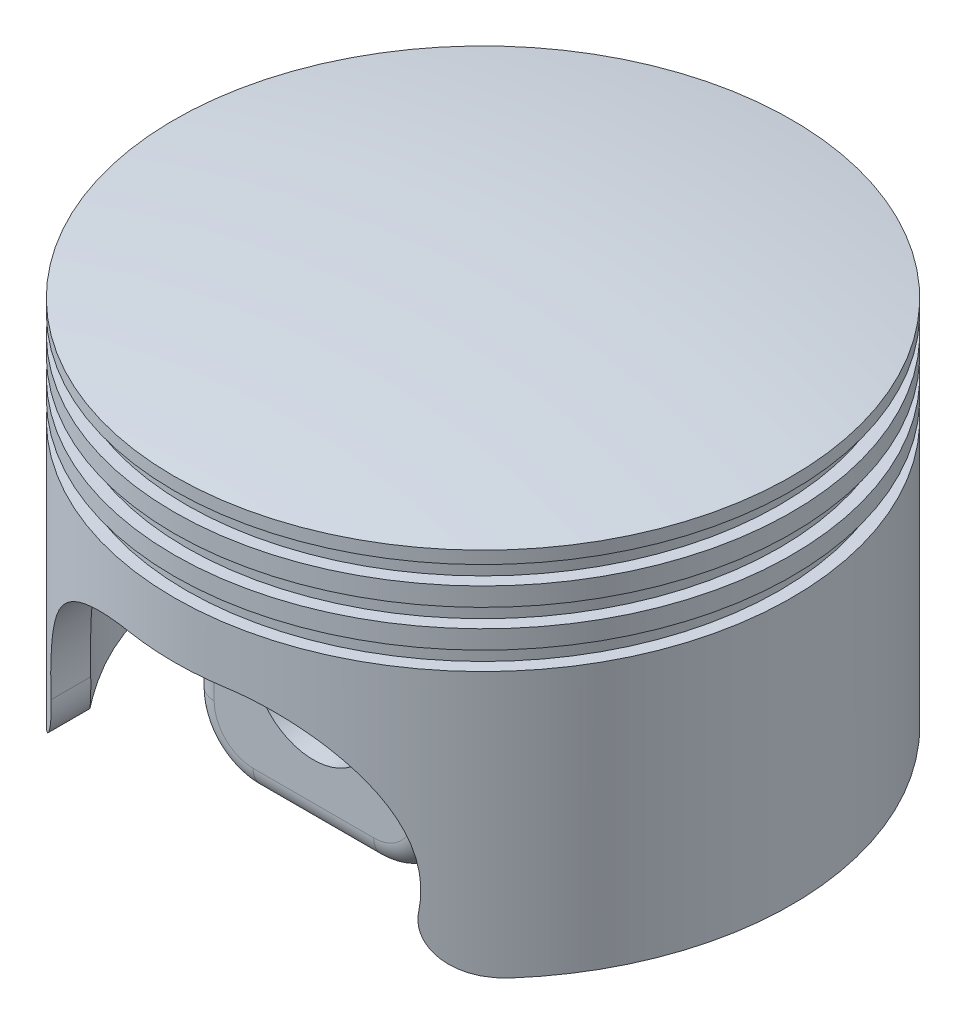
SolidWorks part; units mm, degrees
material "1060 Alloy"
ref_plane "Front Plane" through (0, 0, 0) normal (0, 0, 1) x (1, 0, 0)
ref_plane "Top Plane" through (0, 0, 0) normal (0, 1, 0) x (1, 0, 0)
ref_plane "Right Plane" through (0, 0, 0) normal (1, 0, 0) x (0, 0, -1)
sketch "Sketch1" plane through (0, 0, 0) normal (1, 0, 0) x (0, 0, -1)
  line L0 (0, 0) -> (0, -319.45) construction
  line L1 (-112.706, 0) -> (121.6573, 0) construction
  line L22 (63.5, 0) -> (63.5, 54.66)
  line L23 (63.5, 54.66) -> (60.96, 54.66)
  line L24 (60.96, 54.66) -> (60.96, 58.47)
  line L25 (60.96, 58.47) -> (63.5, 58.47)
  line L26 (63.5, 58.47) -> (63.5, 62.28)
  line L27 (63.5, 62.28) -> (60.96, 62.28)
  line L28 (60.96, 62.28) -> (60.96, 66.09)
  line L29 (60.96, 66.09) -> (63.5, 66.09)
  line L30 (63.5, 66.09) -> (63.5, 69.9)
  line L31 (63.5, 69.9) -> (60.96, 69.9)
  line L32 (60.96, 69.9) -> (60.96, 73.71)
  line L33 (60.96, 73.71) -> (63.5, 73.71)
  line L34 (63.5, 73.71) -> (63.5, 76.28)
  line L36 (0, 76.28) -> (0, 62.28)
  line L37 (0, 76.28) -> (0, 81.28)
  line L38 (63.5, 0) -> (57.15, 0)
  line L39 (57.15, 0) -> (57.15, 62.28)
  line L40 (57.15, 62.28) -> (0, 62.28)
  arc A1 (63.5, 76.28) -> (0, 81.28) centre (-0.0004, -324.45) ccw
  dimension "D2" = 3.81
  dimension "D3" = 3.81
  dimension "D6" = 405.73
  dimension "D9" = 19
  dimension "D1" = 127
  dimension "D4" = 5
  dimension "D5" = 2.54
  dimension "D7" = 81.28
  dimension "D8" = 6.35
revolve "Revolve2" add sketch "Sketch1" angle 360 about L0
sketch "Sketch2" plane through (0, 0, 0) normal (0, 0, 1) x (1, 0, 0)
  line L0 (-10.06, 43.18) -> (10.06, 43.18)
  line L1 (-63.5, 0) -> (63.5, 0) construction
  line L3 (0, 98.8018) -> (0, -12.7881) construction
  line L4 (63.5, 0) -> (47.7053, 0)
  line L5 (-63.5, 0) -> (-47.7053, 0)
  line L6 (-47.7053, 0) -> (47.7053, 0)
  arc A0 (10.06, 43.18) -> (37.7986, 11.3632) centre (10.06, 15.18) cw
  arc A1 (37.7986, 11.3632) -> (47.7053, 0) centre (47.7053, 10) ccw
  arc A2 (-37.7986, 11.3632) -> (-47.7053, 0) centre (-47.7053, 10) cw
  arc A3 (-10.06, 43.18) -> (-37.7986, 11.3632) centre (-10.06, 15.18) ccw
  dimension "D3" = 28
  dimension "D4" = 10
  dimension "D1" = 43.18
  dimension "D2" = 20.12
extrude "Cut-Extrude1" cut sketch "Sketch2" against normal through all both and the other way through all contours L3 L0 A3 A2 L6 | L0 L3 L6 A1 A0
sketch "Sketch3" plane through (0, 62.28, 0) normal (0, -1, 0) x (1, 0, 0)
  line L0 (-72.7421, 0) -> (73.9029, 0) construction
  line L5 (0, 0) -> (0, -45.764) construction
  line L10 (25.4, -34.88) -> (25.4, -15.88)
  line L11 (-25.4, 34.88) -> (25.4, 34.88)
  line L12 (-25.4, 34.88) -> (-25.4, 15.88)
  line L13 (-25.4, 15.88) -> (25.4, 15.88)
  line L14 (25.4, 34.88) -> (25.4, 15.88)
  line L15 (-25.4, -15.88) -> (25.4, -15.88)
  line L16 (-25.4, -34.88) -> (-25.4, -15.88)
  line L17 (-25.4, -34.88) -> (25.4, -34.88)
  dimension "D1" = 50.8
  dimension "D2" = 19
  dimension "D3" = 15.88
extrude "Boss-Extrude1" add sketch "Sketch3" along normal blind 63.5
fillet "Fillet4" radius 13 4 edges at (-25.4, -1.22, 25.38) (25.4, -1.22, 25.38) (-25.4, -1.22, -25.38) (25.4, -1.22, -25.38)
fillet "Fillet5" radius 5 20 edges at (-25.4, 37.03, 15.88) (-21.5924, 2.5876, 15.88) (0, -1.22, 15.88) (21.5924, 2.5876, 15.88) (25.4, 37.03, 34.88) (21.5924, 2.5876, 34.88) (0, -1.22, 34.88) (-21.5924, 2.5876, 34.88) (25.4, 37.03, 15.88) (-25.4, 37.03, 34.88) (-25.4, 37.03, -15.88) (-21.5924, 2.5876, -15.88) (0, -1.22, -15.88) (21.5924, 2.5876, -15.88) (-25.4, 37.03, -34.88) (-21.5924, 2.5876, -34.88) (0, -1.22, -34.88) (21.5924, 2.5876, -34.88) (25.4, 37.03, -15.88) (25.4, 37.03, -34.88)
sketch "Sketch5" plane through (0, 0, -34.88) normal (0, 0, -1) x (-1, 0, 0)
  line L0 (12.4, -1.22) -> (-12.4, -1.22) construction
  circle A0 centre (0, 24.18) radius 12.7
  dimension "D2" = 25.4
  dimension "D1" = 25.4
extrude "Cut-Extrude3" cut sketch "Sketch5" against normal through all both
